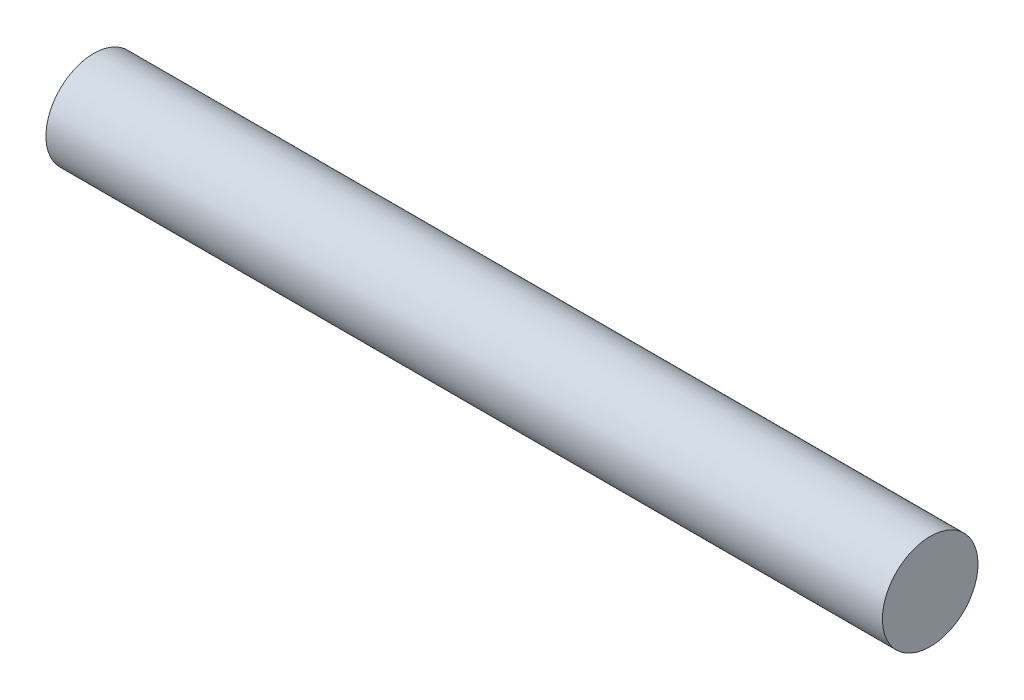
SolidWorks part; units mm, degrees
ref_plane "前视基准面" through (0, 0, 0) normal (0, 0, 1) x (1, 0, 0)
ref_plane "上视基准面" through (0, 0, 0) normal (0, 1, 0) x (1, 0, 0)
ref_plane "右视基准面" through (0, 0, 0) normal (1, 0, 0) x (0, 0, -1)
sketch "草图1" plane through (0, 0, 0) normal (1, 0, 0) x (0, 0, -1)
  circle A0 centre (0, 0) radius 4
extrude "凸台-拉伸1" add sketch "草图1" along normal blind 70
